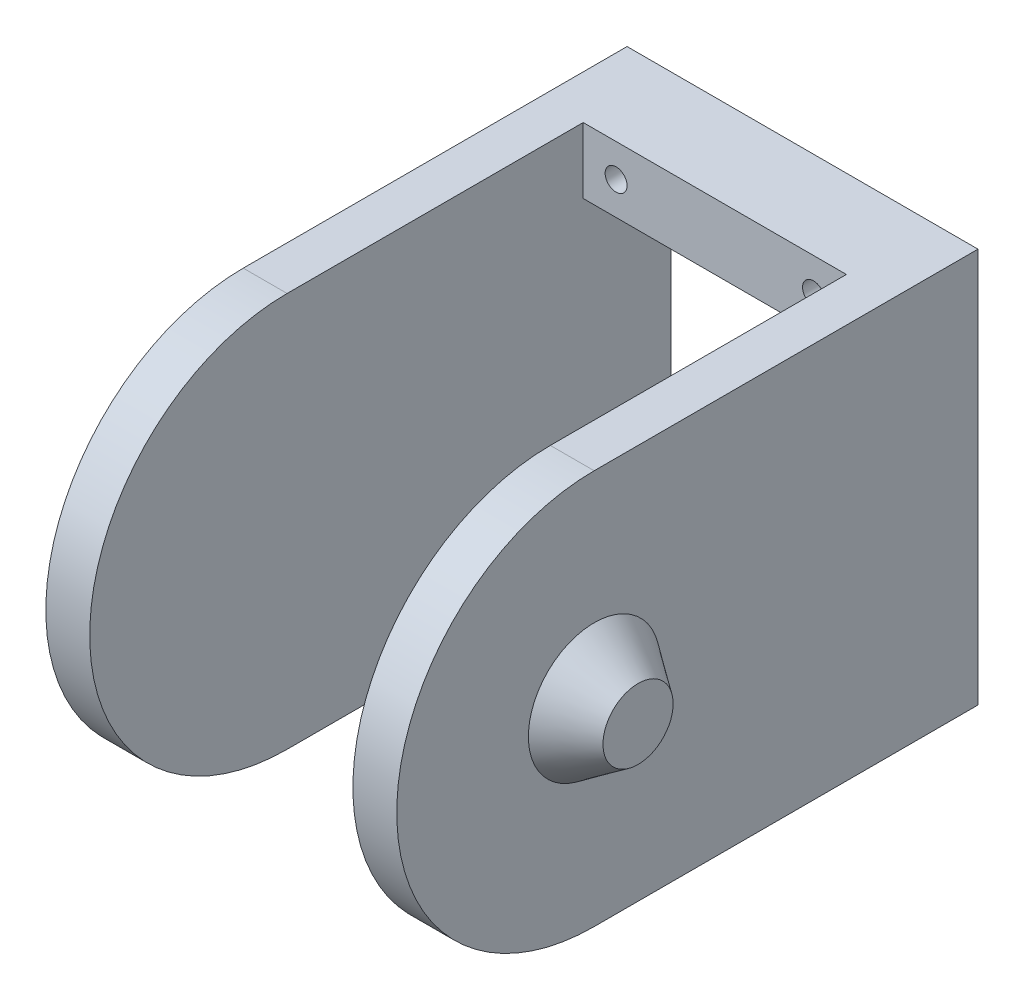
SolidWorks part; units mm, degrees
ref_plane "Front Plane" through (0, 0, 0) normal (0, 0, 1) x (1, 0, 0)
ref_plane "Top Plane" through (0, 0, 0) normal (0, 1, 0) x (1, 0, 0)
ref_plane "Right Plane" through (0, 0, 0) normal (1, 0, 0) x (0, 0, -1)
sketch "Sketch1" plane through (0, 0, 0) normal (0, 0, 1) x (1, 0, 0)
  line L1 (-6, -7) -> (6, -7)
  line L2 (-6, -7) -> (-6, 7)
  line L3 (-6, 7) -> (6, 7)
  line L4 (6, -7) -> (6, 7)
  line L5 (-6, -7) -> (6, 7) construction
  line L6 (-6, 7) -> (6, -7) construction
  point P0 (0, 0)
  dimension "D1" = 12
  dimension "D2" = 14
extrude "Extrude-Thin1" add sketch "Sketch1" along normal mid plane 4 thin
sketch "Sketch2" plane through (8, 0, 0) normal (1, 0, 0) x (0, 0, -1)
  line L1 (2, 9) -> (-15.5, 9)
  line L2 (2, 9) -> (2, -9)
  line L3 (2, -9) -> (-15.5, -9)
  line L5 (2, -9) -> (2, 9) construction
  line L6 (-2, -9) -> (2, -9) construction
  line L8 (2.2, 0) -> (-2.2, 0) construction
  arc A0 (-15.5, 9) -> (-15.5, -9) centre (-15.5, 0) ccw
  dimension "D1" = 17.5
extrude "Boss-Extrude1" add sketch "Sketch2" against normal up to surface (2 mm away) up to face at (6, 0, 0)
sketch "Sketch3" plane through (8, 0, 0) normal (1, 0, 0) x (0, 0, -1)
  line L0 (2.2, 0) -> (-2.2, 0) construction
  circle A0 centre (-15.5, 0) radius 3
  arc A1 (-15.5, 9) -> (-15.5, -9) centre (-15.5, 0) ccw construction
  dimension "D1" = 6
extrude "Boss-Extrude2" add sketch "Sketch3" along normal blind 2 draft 35
sketch "Sketch4" plane through (8, 0, 0) normal (1, 0, 0) x (0, 0, -1)
  line L0 (0, 8.8) -> (0, -8.8) construction
  line L1 (0, 9) -> (17.5, 9)
  line L2 (0, 9) -> (0, -9)
  line L3 (0, -9) -> (17.5, -9)
  line L5 (-15.5, 9) -> (2, 9) construction
  line L6 (-15.5, -9) -> (2, -9) construction
  line L7 (2.2, 0) -> (-2.2, 0) construction
  arc A0 (17.5, 9) -> (17.5, -9) centre (17.5, 0) cw
  dimension "D1" = 17.5
extrude "Boss-Extrude3" [suppressed] add sketch "Sketch4" along normal blind 2.2
sketch "Sketch10" [suppressed] plane through (0, 9, 0) normal (0, 1, 0) x (1, 0, 0)
  line L1 (8, 4) -> (8.2, 4)
  line L2 (8, 4) -> (8, 29.5315)
  line L3 (8, 29.5315) -> (8.2, 29.5315)
  line L4 (8.2, 4) -> (8.2, 29.5315)
  dimension "D1" = 0.2
extrude "Cut-Extrude4" [suppressed] cut sketch "Sketch10" against normal up to next
sketch "Sketch5" [suppressed] plane through (8.2, 0, 0) normal (-1, 0, 0) x (0, 0, 1)
  circle A0 centre (-17.5, 0) radius 3
  dimension "D1" = 6
extrude "Cut-Extrude1" [suppressed] cut sketch "Sketch5" against normal up to next draft 35
mirror "Mirror3" about plane through (0, 0, 0) normal (1, 0, 0) of "Cut-Extrude4", "Boss-Extrude1", "Cut-Extrude1", "Boss-Extrude2", "Extrude-Thin1", "Boss-Extrude3"
sketch "Sketch13" plane through (0, 0, 2) normal (0, 0, 1) x (1, 0, 0)
  line L0 (6, 9) -> (6, -9) construction
  line L1 (-6, 7) -> (6, 7)
  line L2 (-6, 7) -> (-6, 6)
  line L3 (-6, 6) -> (6, 6)
  line L4 (6, 7) -> (6, 6)
  dimension "D1" = 1
extrude "Boss-Extrude4" add sketch "Sketch13" against normal up to surface (4 mm away) up to face at (0, 0, -2)
mirror "Mirror5" about plane through (0, 0, 0) normal (0, 1, 0) of "Boss-Extrude4"
sketch "Sketch11" plane through (0, 0, 2) normal (0, 0, 1) x (1, 0, 0)
  line L0 (-4.5, 9) -> (-4.5, 6) construction
  line L1 (-6, 6) -> (6, 6) construction
  line L2 (6, 9) -> (-6, 9) construction
  line L3 (0, -2.2) -> (0, 2.2) construction
  circle A0 centre (-4.5, 7.5) radius 0.5
  dimension "D2" = 1
  dimension "D1" = 4.5
extrude "Cut-Extrude5" cut sketch "Sketch11" against normal up to next
mirror "Mirror4" about plane through (0, 0, 0) normal (0, 1, 0) of "Cut-Extrude5" second plane through (0, 0, 0) second plane normal (1, 0, 0)
